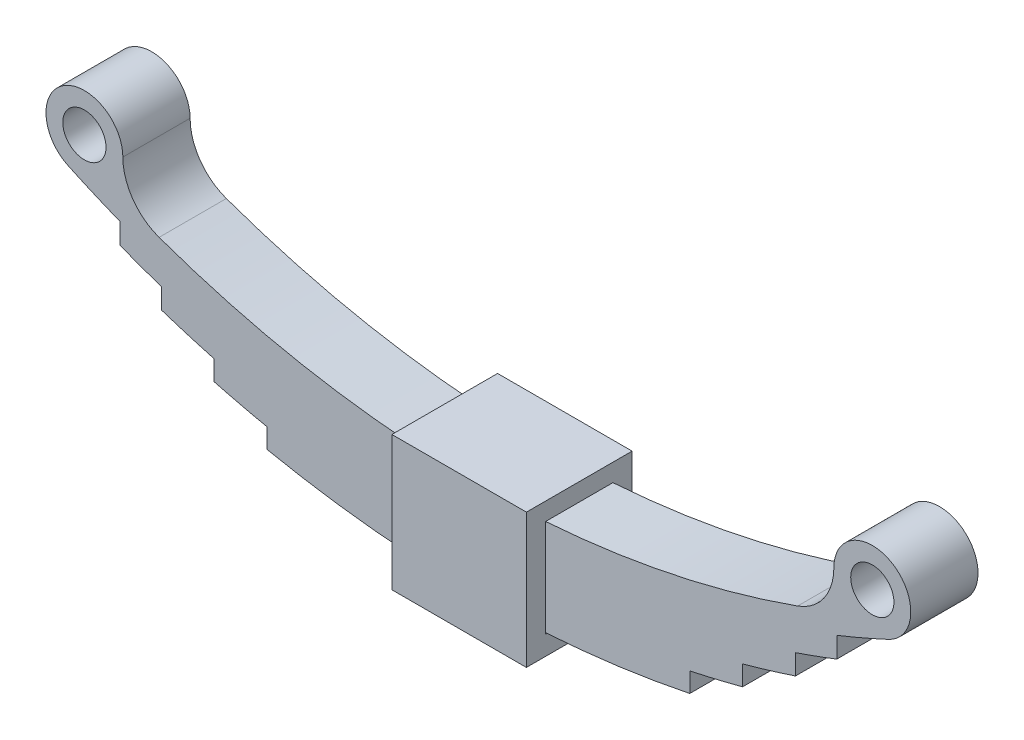
SolidWorks part; units mm, degrees
ref_plane "Front Plane" through (0, 0, 0) normal (0, 0, 1) x (1, 0, 0)
ref_plane "Top Plane" through (0, 0, 0) normal (0, 1, 0) x (1, 0, 0)
ref_plane "Right Plane" through (0, 0, 0) normal (1, 0, 0) x (0, 0, -1)
sketch "Sketch1" plane through (0, 0, 0) normal (0, 0, 1) x (1, 0, 0)
  line L0 (-41, 0) -> (0, 0) construction
  line L1 (0, 0) -> (0, 87.909) construction
  line L2 (0, -11.091) -> (0, -13.091)
  line L3 (-37.3, -8.0999) -> (-37.3, -5.951)
  line L4 (0, 0) -> (0, -11.091) construction
  line L5 (0, -15.091) -> (0, -17.091)
  line L6 (0, -17.091) -> (0, -19.091)
  line L7 (0, -19.091) -> (0, -21.091)
  line L8 (-33, -11.7704) -> (-33, -9.6614)
  line L9 (-27.5, -15.4967) -> (-27.5, -13.4258)
  line L10 (-22, -18.8477) -> (-22, -16.8049)
  line L11 (0, -13.091) -> (0, -15.091)
  circle A0 centre (-41, 0) radius 2.25
  arc A2 (-33.2281, -5.3481) -> (0, -11.091) centre (0, 87.909) ccw
  arc A3 (-42.6907, -3.6251) -> (0, -13.091) centre (0, 87.909) ccw construction
  arc A5 (-42.6907, -3.6251) -> (-37, 0) centre (-41, 0) cw
  arc A7 (-33.2281, -5.3481) -> (-37, 0) centre (-31.3226, 0) cw
  arc A8 (-37.3, -8.0999) -> (0, -15.091) centre (0, 87.909) ccw construction
  arc A9 (-33, -11.7704) -> (0, -17.091) centre (0, 87.909) ccw construction
  arc A10 (-27.5, -15.4967) -> (0, -19.091) centre (0, 87.909) ccw construction
  arc A11 (-22, -18.8477) -> (0, -21.091) centre (0, 87.909) ccw
  arc A12 (-42.6907, -3.6251) -> (-37.3, -5.951) centre (0, 87.909) ccw
  arc A13 (-37.3, -8.0999) -> (-33, -9.6614) centre (0, 87.909) ccw
  arc A14 (-33, -11.7704) -> (-27.5, -13.4258) centre (0, 87.909) ccw
  arc A15 (-27.5, -15.4967) -> (-22, -16.8049) centre (0, 87.909) ccw
  dimension "D2" = 4.5
  dimension "D3" = 2
  dimension "D4" = 4
  dimension "D5" = 99
  dimension "D6" = 2
  dimension "D8" = 2
  dimension "D7" = 41
  dimension "D9" = 2
  dimension "D10" = 2
  dimension "D11" = 37.3
  dimension "D12" = 33
  dimension "D13" = 27.5
  dimension "D14" = 22
extrude "Boss-Extrude2" add sketch "Sketch1" along normal blind 7 contours A2 L2 L11 L5 L6 L7 A11 L10 A15 L9 A14 L8 A13 L3 A12 A5 A7 | A0
mirror "Mirror1" about plane through (0, -11.091, 7) normal (1, 0, 0) of bodies 102
sketch "Sketch4" plane through (0, 0, 0) normal (1, 0, 0) x (0, 0, -1)
  line L0 (0, 0) -> (-3.5, 0) construction
  line L1 (2, -9) -> (-9, -9)
  line L2 (2, -9) -> (2, -23)
  line L3 (2, -23) -> (-9, -23)
  line L4 (-9, -9) -> (-9, -23)
  line L5 (0, -11) -> (-7, -11)
  line L6 (0, -11) -> (0, -21)
  line L7 (0, -21) -> (-7, -21)
  line L8 (-7, -11) -> (-7, -21)
  line L9 (-3.5, 0) -> (-3.5, -9) construction
  line L10 (-3.5, -9) -> (-3.5, -11) construction
  dimension "D1" = 3.5
  dimension "D2" = 2
  dimension "D3" = 9
  dimension "D4" = 2
  dimension "D5" = 2
  dimension "D6" = 14
  dimension "D7" = 11
extrude "Boss-Extrude3" add sketch "Sketch4" along normal mid plane 14
sketch "Sketch5" plane through (0, -23, 0) normal (0, -1, 0) x (1, 0, 0)
  line L0 (7, 3.5) -> (0, 3.5) construction
  line L1 (7, 9) -> (7, -2) construction
  line L2 (0, 3.5) -> (0, 9) construction
  line L3 (7, 9) -> (-7, 9) construction
  circle A0 centre (0, 3.5) radius 4
  dimension "D1" = 8
extrude "Cut-Extrude1" cut sketch "Sketch5" against normal blind 11
